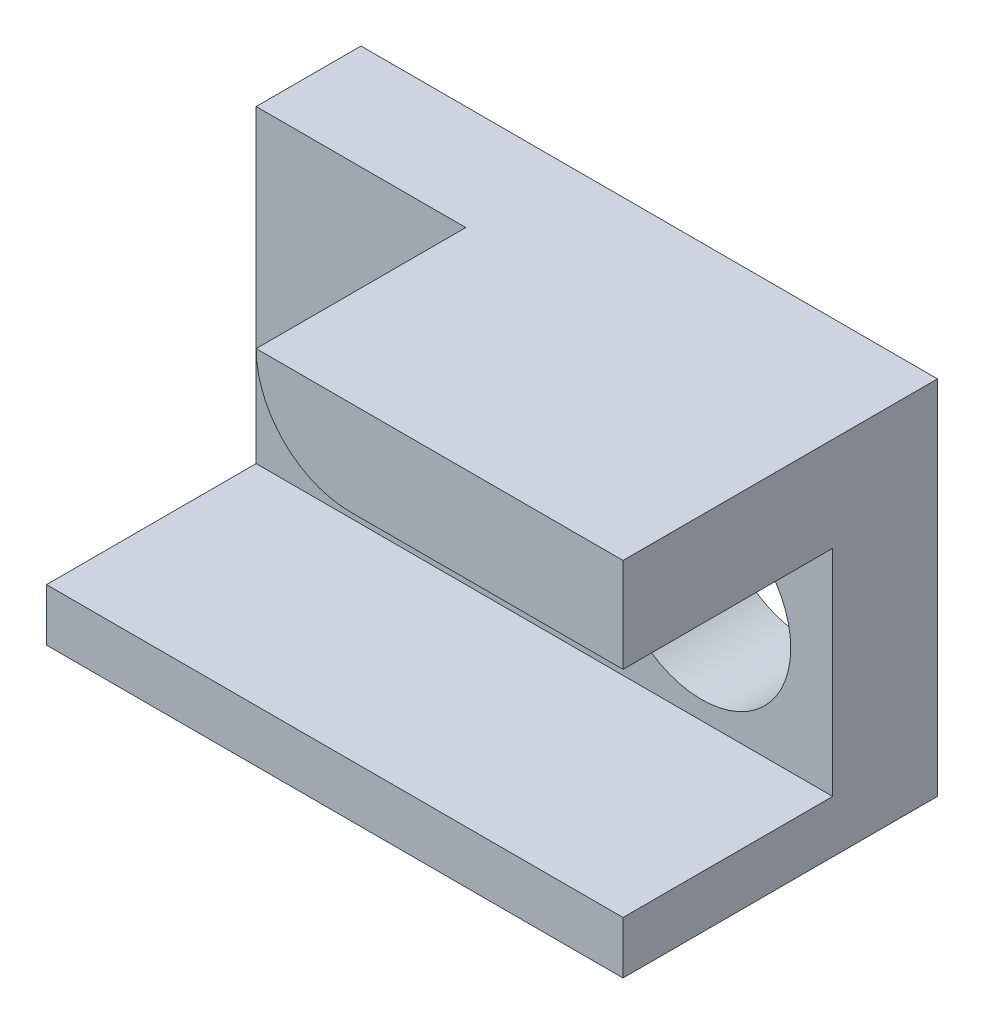
SolidWorks part; units mm, degrees
ref_plane "Front Plane" through (0, 0, 0) normal (0, 0, 1) x (1, 0, 0)
ref_plane "Top Plane" through (0, 0, 0) normal (0, 1, 0) x (1, 0, 0)
ref_plane "Right Plane" through (0, 0, 0) normal (1, 0, 0) x (0, 0, -1)
sketch "Sketch2" plane through (0, 0, 0) normal (0, 0, 1) x (1, 0, 0)
  line L1 (0, 4.1) -> (0, 5.1)
  line L2 (0, 0) -> (0, -1)
  line L3 (0, -1) -> (-11, -1)
  line L4 (0, 0) -> (-11, 0)
  line L5 (-11, -1) -> (-11, 0)
  line L7 (0, 4.1) -> (-5, 4.1)
  line L9 (-7, 5.9) -> (0, 5.9)
  line L10 (0, 5.9) -> (0, 4.1)
  line L11 (-5, 4.1) -> (-5.2, 4.1)
  line L13 (-5, 4.1) -> (0, 4.1)
  line L15 (-5, 5.9) -> (-7, 5.9)
  arc A0 (-5.2, 4.1) -> (-7, 5.9) centre (-5.2, 5.9) cw
  dimension "D8" = 1.8
  dimension "D1" = 4.1
  dimension "D2" = 1
  dimension "D3" = 1
  dimension "D4" = 11
  dimension "D6" = 5
extrude "Boss-Extrude1" add sketch "Sketch2" along normal blind 4 contours A0 L11 L7 L1 L10 L9 | L5 L3 L2 L4
sketch "Sketch3" plane through (0, 0, 0) normal (0, 0, -1) x (-1, 0, 0)
  line L1 (0, 5.9) -> (11, 5.9)
  line L2 (0, 5.9) -> (0, -1)
  line L3 (0, -1) -> (11, -1)
  line L4 (11, 5.9) -> (11, -1)
extrude "Boss-Extrude2" add sketch "Sketch3" along normal blind 2
sketch "Sketch5" plane through (0, 0, 0) normal (0, 0, 1) x (1, 0, 0)
  line L0 (0, 4.1) -> (0, 0)
  line L1 (0, 2.05) -> (-2.5, 2.05)
  circle A0 centre (-2.5, 2.05) radius 1.7
  dimension "D2" = 3.4
  dimension "D1" = 2.5
extrude "Cut-Extrude1" cut sketch "Sketch5" against normal blind 2
